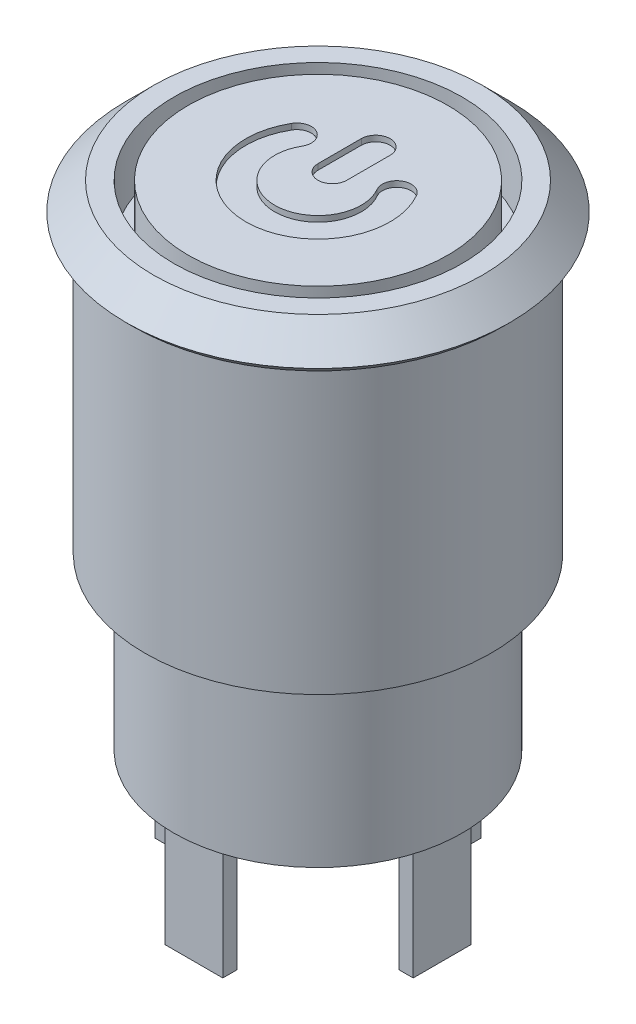
SolidWorks part; units mm, degrees
ref_plane "前视基准面" through (0, 0, 0) normal (0, 0, 1) x (1, 0, 0)
ref_plane "上视基准面" through (0, 0, 0) normal (0, 1, 0) x (1, 0, 0)
ref_plane "右视基准面" through (0, 0, 0) normal (1, 0, 0) x (0, 0, -1)
other "Configuration Table"
sketch "草图1" plane through (0, 0, 0) normal (0, 1, 0) x (1, 0, 0)
  circle A0 centre (0, 0) radius 6
  dimension "D1" = 12
extrude "凸台-拉伸1" add sketch "草图1" along normal blind 10
ref_plane "基准面1" through (0, 11.2, 0) normal (0, 1, 0) x (1, 0, 0)
sketch "草图2" plane through (0, 11.2, 0) normal (0, 1, 0) x (1, 0, 0)
  circle A0 centre (0, 0) radius 5.7
  dimension "D1" = 11.4
sketch "草图3" plane through (0, 10, 0) normal (0, 1, 0) x (1, 0, 0)
  circle A0 centre (0, 0) radius 6.9
  dimension "D1" = 13.8
loft "放样1" add profiles "草图2", "草图3"
chamfer "倒角1" distance 0.5 angle 45 1 edges at (0, 10, 6.9)
sketch "草图4" plane through (0, 11.2, 0) normal (0, 1, 0) x (1, 0, 0)
  circle A0 centre (0, 0) radius 5
  dimension "D1" = 10
extrude "切除-拉伸1" cut sketch "草图4" against normal blind 2
sketch "草图5" plane through (0, 9.2, 0) normal (0, 1, 0) x (1, 0, 0)
  circle A0 centre (0, 0) radius 4.5
  dimension "D1" = 9
extrude "凸台-拉伸2" add sketch "草图5" along normal blind 2
sketch "草图6" plane through (0, 11.2, 0) normal (0, 1, 0) x (1, 0, 0)
  line L0 (0, 0) -> (-2.1651, 1.25) construction
  line L1 (0, 0) -> (0, 3.1056) construction
  line L2 (0, 0) -> (2.1651, 1.25) construction
  line L3 (-0.5, 0.5) -> (-0.5, 2)
  line L4 (0.5, 0.5) -> (0.5, 2)
  arc A0 (-2.1651, 1.25) -> (2.1651, 1.25) centre (0, 0) ccw
  arc A1 (-1.299, 0.75) -> (1.299, 0.75) centre (0, 0) ccw
  arc A2 (-2.1651, 1.25) -> (-1.299, 0.75) centre (-1.7321, 1) cw
  arc A3 (2.1651, 1.25) -> (1.299, 0.75) centre (1.7321, 1) ccw
  arc A4 (-0.5, 2) -> (0.5, 2) centre (0, 2) cw
  arc A5 (0.5, 0.5) -> (-0.5, 0.5) centre (0, 0.5) cw
  point P14 (0, 0)
  point P16 (0, 0.5085)
  point P17 (0, 0)
  point P18 (0, 0)
  dimension "D1" = 5
  dimension "D2" = 3
  dimension "D3" = 60
  dimension "D4" = 60
  dimension "D5" = 1
  dimension "D6" = 1.5
extrude "切除-拉伸2" cut sketch "草图6" against normal blind 0.2
sketch "草图20" plane through (0, 0, 0) normal (0, -1, 0) x (1, 0, 0)
  circle A0 centre (0, 0) radius 5
  dimension "D1" = 10
extrude "凸台-拉伸3" add sketch "草图20" along normal blind 5.9
sketch "草图21" plane through (0, -5.9, 0) normal (0, -1, 0) x (1, 0, 0)
  line L0 (-2.1937, 0) -> (3.1577, 0) construction
  line L1 (-1, 4.3) -> (1, 4.3)
  line L2 (-1, 4.3) -> (-1, 3.8)
  line L3 (-1, 3.8) -> (1, 3.8)
  line L4 (1, 4.3) -> (1, 3.8)
  line L5 (-1, 4.3) -> (1, 3.8) construction
  line L6 (-1, 3.8) -> (1, 4.3) construction
  line L7 (-1.2771, -3.8) -> (1.2771, -3.8)
  line L8 (-1.2771, -3.8) -> (-1.2771, -4.381)
  line L9 (-1.2771, -4.381) -> (1.2771, -4.381)
  line L10 (1.2771, -3.8) -> (1.2771, -4.381)
  line L11 (-1.2771, -3.8) -> (1.2771, -4.381) construction
  line L12 (-1.2771, -4.381) -> (1.2771, -3.8) construction
  line L13 (3.8, 1) -> (3.8, -1)
  line L14 (4.3, 1) -> (3.8, 1)
  line L15 (4.3, 1) -> (4.3, -1)
  line L16 (4.3, -1) -> (3.8, -1)
  line L17 (-3.8, 1.2771) -> (-3.8, -1.2771)
  line L18 (-3.8, -1.2771) -> (-4.381, -1.2771)
  line L19 (-4.381, 1.2771) -> (-4.381, -1.2771)
  line L20 (-3.8, 1.2771) -> (-4.381, 1.2771)
  point P0 (0, 4.05)
  point P5 (0, -4.0905)
  point P24 (0, 0)
  dimension "D1" = 7.6
  dimension "D2" = 2
  dimension "D3" = 0.5
  dimension "D4" = 2
extrude "凸台-拉伸4" add sketch "草图21" along normal blind 4.2
